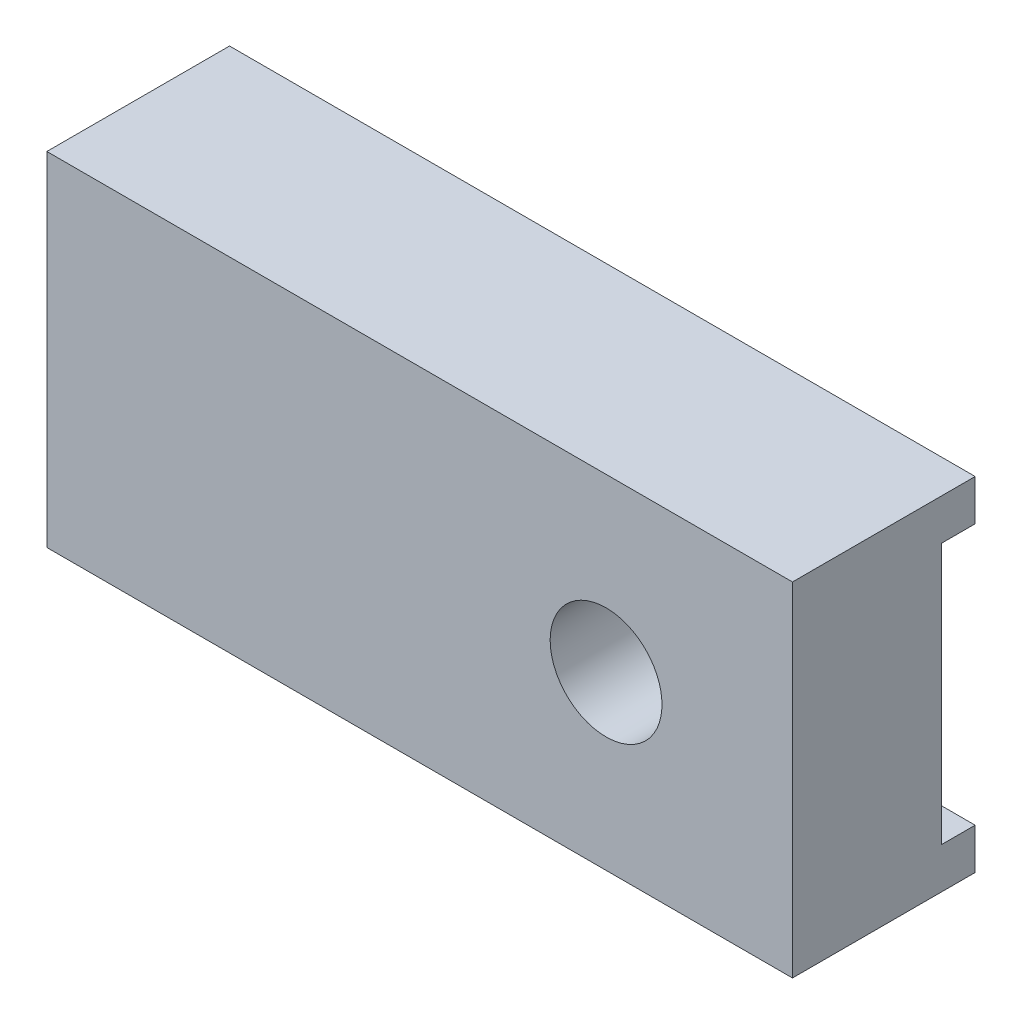
SolidWorks part; units mm, degrees
other "Câmera1"
ref_plane "Plano frontal" through (0, 0, 0) normal (0, 0, 1) x (1, 0, 0)
ref_plane "Plano superior" through (0, 0, 0) normal (0, 1, 0) x (1, 0, 0)
ref_plane "Plano direito" through (0, 0, 0) normal (1, 0, 0) x (0, 0, -1)
sketch "Esboço4" plane through (0, 0, 0) normal (0, 1, 0) x (1, 0, 0)
  line L0 (-19.2, 2.35) -> (-19.2, 1.65)
  line L1 (-20, -2.45) -> (20, -2.45)
  line L2 (-20, -2.45) -> (-20, 2.35)
  line L3 (-19.9, 2.45) -> (-19.3, 2.45)
  line L4 (20, -2.45) -> (20, 2.35)
  line L5 (-19.1, 1.55) -> (-18.1, 1.55)
  line L6 (19.2, 2.35) -> (19.2, 1.65)
  line L7 (19.3, 2.45) -> (19.9, 2.45)
  line L8 (-18, 1.65) -> (-18, 2.35)
  line L9 (-17.9, 2.45) -> (-17.3, 2.45)
  line L10 (-17.2, 2.35) -> (-17.2, 1.65)
  line L11 (-16, 1.65) -> (-16, 2.35)
  line L12 (-15.9, 2.45) -> (-15.3, 2.45)
  line L13 (-15.2, 2.35) -> (-15.2, 1.65)
  line L14 (-14, 1.65) -> (-14, 2.35)
  line L15 (-13.9, 2.45) -> (-13.3, 2.45)
  line L16 (-13.2, 2.35) -> (-13.2, 1.65)
  line L17 (-12, 1.65) -> (-12, 2.35)
  line L18 (-11.9, 2.45) -> (-11.3, 2.45)
  line L19 (-11.2, 2.35) -> (-11.2, 1.65)
  line L20 (-10, 1.65) -> (-10, 2.35)
  line L21 (-9.9, 2.45) -> (-9.3, 2.45)
  line L22 (-9.2, 2.35) -> (-9.2, 1.65)
  line L23 (-8, 1.65) -> (-8, 2.35)
  line L24 (-7.9, 2.45) -> (-7.3, 2.45)
  line L25 (-7.2, 2.35) -> (-7.2, 1.65)
  line L26 (-7.1, 1.55) -> (7.1, 1.55)
  line L27 (-9.1, 1.55) -> (-8.1, 1.55)
  line L28 (-11.1, 1.55) -> (-10.1, 1.55)
  line L29 (-13.1, 1.55) -> (-12.1, 1.55)
  line L30 (-15.1, 1.55) -> (-14.1, 1.55)
  line L31 (-17.1, 1.55) -> (-16.1, 1.55)
  line L32 (17.2, 2.35) -> (17.2, 1.65)
  line L33 (17.3, 2.45) -> (17.9, 2.45)
  line L34 (18, 1.65) -> (18, 2.35)
  line L35 (15.2, 2.35) -> (15.2, 1.65)
  line L36 (15.3, 2.45) -> (15.9, 2.45)
  line L37 (16, 1.65) -> (16, 2.35)
  line L38 (13.2, 2.35) -> (13.2, 1.65)
  line L39 (13.3, 2.45) -> (13.9, 2.45)
  line L40 (14, 1.65) -> (14, 2.35)
  line L41 (11.2, 2.35) -> (11.2, 1.65)
  line L42 (11.3, 2.45) -> (11.9, 2.45)
  line L43 (12, 1.65) -> (12, 2.35)
  line L44 (9.2, 2.35) -> (9.2, 1.65)
  line L45 (9.3, 2.45) -> (9.9, 2.45)
  line L46 (10, 1.65) -> (10, 2.35)
  line L47 (7.2, 2.35) -> (7.2, 1.65)
  line L48 (7.3, 2.45) -> (7.9, 2.45)
  line L49 (8, 1.65) -> (8, 2.35)
  line L50 (8.1, 1.55) -> (9.1, 1.55)
  line L51 (10.1, 1.55) -> (11.1, 1.55)
  line L52 (12.1, 1.55) -> (13.1, 1.55)
  line L53 (14.1, 1.55) -> (15.1, 1.55)
  line L54 (16.1, 1.55) -> (17.1, 1.55)
  line L55 (18.1, 1.55) -> (19.1, 1.55)
  arc A0 (19.9, 2.45) -> (20, 2.35) centre (19.9, 2.35) cw
  arc A1 (19.2, 2.35) -> (19.3, 2.45) centre (19.3, 2.35) cw
  arc A2 (19.1, 1.55) -> (19.2, 1.65) centre (19.1, 1.65) ccw
  arc A3 (18.1, 1.55) -> (18, 1.65) centre (18.1, 1.65) cw
  arc A4 (17.9, 2.45) -> (18, 2.35) centre (17.9, 2.35) cw
  arc A5 (17.2, 2.35) -> (17.3, 2.45) centre (17.3, 2.35) cw
  arc A6 (17.2, 1.65) -> (17.1, 1.55) centre (17.1, 1.65) cw
  arc A7 (16.1, 1.55) -> (16, 1.65) centre (16.1, 1.65) cw
  arc A8 (15.9, 2.45) -> (16, 2.35) centre (15.9, 2.35) cw
  arc A9 (15.2, 2.35) -> (15.3, 2.45) centre (15.3, 2.35) cw
  arc A10 (15.2, 1.65) -> (15.1, 1.55) centre (15.1, 1.65) cw
  arc A11 (14, 1.65) -> (14.1, 1.55) centre (14.1, 1.65) ccw
  arc A12 (13.9, 2.45) -> (14, 2.35) centre (13.9, 2.35) cw
  arc A13 (13.2, 2.35) -> (13.3, 2.45) centre (13.3, 2.35) cw
  arc A14 (13.2, 1.65) -> (13.1, 1.55) centre (13.1, 1.65) cw
  arc A15 (12, 1.65) -> (12.1, 1.55) centre (12.1, 1.65) ccw
  arc A16 (11.9, 2.45) -> (12, 2.35) centre (11.9, 2.35) cw
  arc A17 (11.2, 2.35) -> (11.3, 2.45) centre (11.3, 2.35) cw
  arc A18 (11.2, 1.65) -> (11.1, 1.55) centre (11.1, 1.65) cw
  arc A19 (10, 1.65) -> (10.1, 1.55) centre (10.1, 1.65) ccw
  arc A20 (9.9, 2.45) -> (10, 2.35) centre (9.9, 2.35) cw
  arc A21 (9.2, 2.35) -> (9.3, 2.45) centre (9.3, 2.35) cw
  arc A22 (9.2, 1.65) -> (9.1, 1.55) centre (9.1, 1.65) cw
  arc A23 (8, 1.65) -> (8.1, 1.55) centre (8.1, 1.65) ccw
  arc A24 (7.9, 2.45) -> (8, 2.35) centre (7.9, 2.35) cw
  arc A25 (7.2, 2.35) -> (7.3, 2.45) centre (7.3, 2.35) cw
  arc A26 (7.2, 1.65) -> (7.1, 1.55) centre (7.1, 1.65) cw
  arc A27 (-7.2, 1.65) -> (-7.1, 1.55) centre (-7.1, 1.65) ccw
  arc A28 (-7.3, 2.45) -> (-7.2, 2.35) centre (-7.3, 2.35) cw
  arc A29 (-8, 1.65) -> (-8.1, 1.55) centre (-8.1, 1.65) cw
  arc A30 (-8, 2.35) -> (-7.9, 2.45) centre (-7.9, 2.35) cw
  arc A31 (-9.2, 1.65) -> (-9.1, 1.55) centre (-9.1, 1.65) ccw
  arc A32 (-9.3, 2.45) -> (-9.2, 2.35) centre (-9.3, 2.35) cw
  arc A33 (-10, 2.35) -> (-9.9, 2.45) centre (-9.9, 2.35) cw
  arc A34 (-10, 1.65) -> (-10.1, 1.55) centre (-10.1, 1.65) cw
  arc A35 (-11.2, 1.65) -> (-11.1, 1.55) centre (-11.1, 1.65) ccw
  arc A36 (-11.3, 2.45) -> (-11.2, 2.35) centre (-11.3, 2.35) cw
  arc A37 (-12, 1.65) -> (-12.1, 1.55) centre (-12.1, 1.65) cw
  arc A38 (-12, 2.35) -> (-11.9, 2.45) centre (-11.9, 2.35) cw
  arc A39 (-13.2, 1.65) -> (-13.1, 1.55) centre (-13.1, 1.65) ccw
  arc A40 (-13.3, 2.45) -> (-13.2, 2.35) centre (-13.3, 2.35) cw
  arc A41 (-14, 1.65) -> (-14.1, 1.55) centre (-14.1, 1.65) cw
  arc A42 (-14, 2.35) -> (-13.9, 2.45) centre (-13.9, 2.35) cw
  arc A43 (-15.2, 1.65) -> (-15.1, 1.55) centre (-15.1, 1.65) ccw
  arc A44 (-15.3, 2.45) -> (-15.2, 2.35) centre (-15.3, 2.35) cw
  arc A45 (-16, 1.65) -> (-16.1, 1.55) centre (-16.1, 1.65) cw
  arc A46 (-16, 2.35) -> (-15.9, 2.45) centre (-15.9, 2.35) cw
  arc A47 (-17.2, 1.65) -> (-17.1, 1.55) centre (-17.1, 1.65) ccw
  arc A48 (-17.3, 2.45) -> (-17.2, 2.35) centre (-17.3, 2.35) cw
  arc A49 (-18, 1.65) -> (-18.1, 1.55) centre (-18.1, 1.65) cw
  arc A50 (-18, 2.35) -> (-17.9, 2.45) centre (-17.9, 2.35) cw
  arc A51 (-19.2, 1.65) -> (-19.1, 1.55) centre (-19.1, 1.65) ccw
  arc A52 (-19.2, 2.35) -> (-19.3, 2.45) centre (-19.3, 2.35) ccw
  arc A53 (-20, 2.35) -> (-19.9, 2.45) centre (-19.9, 2.35) cw
  point P0 (0, 0)
  point P62 (19.2, 2.45)
  point P83 (14, 1.55)
  point P92 (12, 1.55)
  point P101 (10, 1.55)
  point P110 (8, 1.55)
  dimension "D2" = 0.1
  dimension "D1" = 7
extrude "Ressalto-extrusão2" add sketch "Esboço4" along normal blind 9.2
sketch "Esboço5" plane through (0, 0, -1.55) normal (0, 0, -1) x (-1, 0, 0)
  circle A0 centre (0, 4.6) radius 2.15
  dimension "D1" = 4.3
extrude "Corte-extrusão2" cut sketch "Esboço5" against normal blind 9.2
chamfer "Chanfro2" distance 0.3 angle 45 1 edges at (-2.15, 4.6, -1.55)
sketch "Sketch1" plane through (20, 0, 0) normal (1, 0, 0) x (0, 0, -1)
  line L1 (5.7525, 12.1439) -> (-6.2616, 12.1439)
  line L2 (5.7525, 12.1439) -> (5.7525, -5.0794)
  line L3 (5.7525, -5.0794) -> (-6.2616, -5.0794)
  line L4 (-6.2616, 12.1439) -> (-6.2616, -5.0794)
extrude "Cut-Extrude1" cut sketch "Sketch1" against normal blind 25
sketch "Sketch3" plane through (-5, 0, 0) normal (1, 0, 0) x (0, 0, -1)
  line L1 (1.55, 9.2) -> (-2.45, 9.2)
  line L2 (1.55, 9.2) -> (1.55, 0)
  line L3 (1.55, 0) -> (-2.45, 0)
  line L4 (-2.45, 9.2) -> (-2.45, 0)
extrude "Boss-Extrude1" add sketch "Sketch3" along normal blind 5
sketch "Sketch4" plane through (0, 0, -1.55) normal (0, 0, -1) x (-1, 0, 0)
  line L0 (0, 4.6) -> (5, 4.6)
  line L1 (0, 0) -> (0, 9.2) construction
  circle A0 centre (5, 4.6) radius 1.5
  dimension "D1" = 5
extrude "Cut-Extrude3" cut sketch "Sketch4" against normal blind 10
sketch "Sketch5" plane through (0, 0, 0) normal (0, -1, 0) x (1, 0, 0)
  line L1 (-33.582, -23.2473) -> (9.0238, -23.2473)
  line L2 (-33.582, -23.2473) -> (-33.582, 10.2625)
  line L3 (-33.582, 10.2625) -> (9.0238, 10.2625)
  line L4 (9.0238, -23.2473) -> (9.0238, 10.2625)
extrude "Cut-Extrude4" cut sketch "Sketch5" against normal blind 1.1
sketch "Sketch6" plane through (0, 9.2, 0) normal (0, 1, 0) x (1, 0, 0)
  line L1 (-34.3682, -9.243) -> (23.8083, -9.243)
  line L2 (-34.3682, -9.243) -> (-34.3682, 16.6451)
  line L3 (-34.3682, 16.6451) -> (23.8083, 16.6451)
  line L4 (23.8083, -9.243) -> (23.8083, 16.6451)
extrude "Cut-Extrude5" cut sketch "Sketch6" against normal blind 1.1
sketch "Sketch7" plane through (0, 8.1, 0) normal (0, 1, 0) x (1, 0, 0)
  line L1 (-20, -2.45) -> (0, -2.45)
  line L2 (-20, -2.45) -> (-20, 2.45)
  line L3 (-20, 2.45) -> (0, 2.45)
  line L4 (0, -2.45) -> (0, 2.45)
  dimension "D1" = 4.9
extrude "Boss-Extrude2" add sketch "Sketch7" along normal blind 1.1
sketch "Sketch8" plane through (0, 1.1, 0) normal (0, -1, 0) x (1, 0, 0)
  line L1 (-20, 2.45) -> (0, 2.45)
  line L2 (-20, 2.45) -> (-20, -2.45)
  line L3 (-20, -2.45) -> (0, -2.45)
  line L4 (0, 2.45) -> (0, -2.45)
  dimension "D1" = 4.9
extrude "Boss-Extrude3" add sketch "Sketch8" along normal blind 1.1
